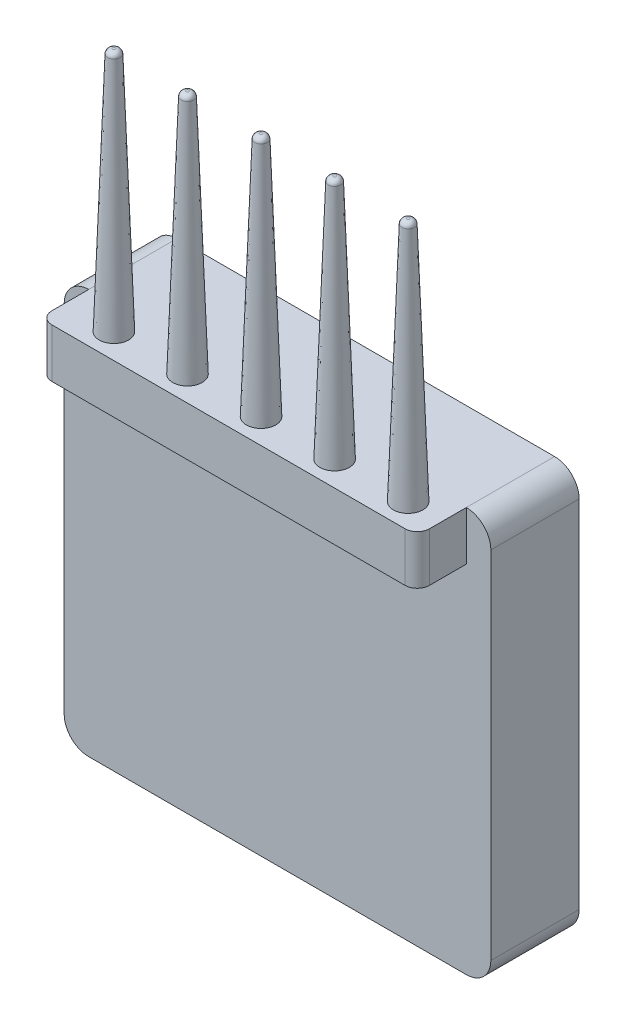
SolidWorks part; units mm, degrees
ref_plane "정면" through (0, 0, 0) normal (0, 0, 1) x (1, 0, 0)
ref_plane "윗면" through (0, 0, 0) normal (0, 1, 0) x (1, 0, 0)
ref_plane "우측면" through (0, 0, 0) normal (1, 0, 0) x (0, 0, -1)
sketch "스케치1" plane through (0, 0, 0) normal (0, 0, 1) x (1, 0, 0)
  line L1 (-77, -82.5) -> (77, -82.5)
  line L2 (-87, -72.5) -> (-87, 72.5)
  line L3 (-77, 82.5) -> (77, 82.5)
  line L4 (87, -72.5) -> (87, 72.5)
  line L5 (-87, -82.5) -> (87, 82.5) construction
  line L6 (-87, 82.5) -> (87, -82.5) construction
  arc A0 (-77, -82.5) -> (-87, -72.5) centre (-77, -72.5) cw
  arc A1 (77, -82.5) -> (87, -72.5) centre (77, -72.5) ccw
  arc A2 (77, 82.5) -> (87, 72.5) centre (77, 72.5) cw
  arc A3 (-87, 72.5) -> (-77, 82.5) centre (-77, 72.5) cw
  point P0 (0, 0)
  dimension "D3" = 10
  dimension "D1" = 174
  dimension "D2" = 165
extrude "보스-돌출1" add sketch "스케치1" along normal blind 36
sketch "스케치3" plane through (0, 0, 36) normal (0, 0, 1) x (1, 0, 0)
  line L1 (-77, 82.5) -> (77, 82.5)
  line L2 (-77, 82.5) -> (-77, 62.5)
  line L3 (-77, 62.5) -> (77, 62.5)
  line L4 (77, 82.5) -> (77, 62.5)
  dimension "D1" = 20
extrude "보스-돌출4" add sketch "스케치3" along normal blind 20
sketch "스케치4" plane through (0, 82.5, 0) normal (0, 1, 0) x (1, 0, 0)
  line L0 (-77, -56) -> (-77, -36) construction
  circle A0 centre (-57, -45.7165) radius 6
  circle A1 centre (-27, -45.7165) radius 6
  circle A2 centre (3, -45.7165) radius 6
  circle A3 centre (33, -45.7165) radius 6
  circle A4 centre (63, -45.7165) radius 6
  dimension "D1" = 20
  dimension "D2" = 30
  dimension "D3" = 30
  dimension "D4" = 30
  dimension "D5" = 30
extrude "보스-돌출5" add sketch "스케치4" along normal blind 100 draft 2
fillet "필렛1" radius 2 5 edges at (63, 182.5, 48.2244) (33, 182.5, 48.2244) (3, 182.5, 48.2244) (-27, 182.5, 48.2244) (-57, 182.5, 48.2244)
fillet "필렛2" radius 5 2 edges at (-77, 72.5, 56) (77, 72.5, 56)
